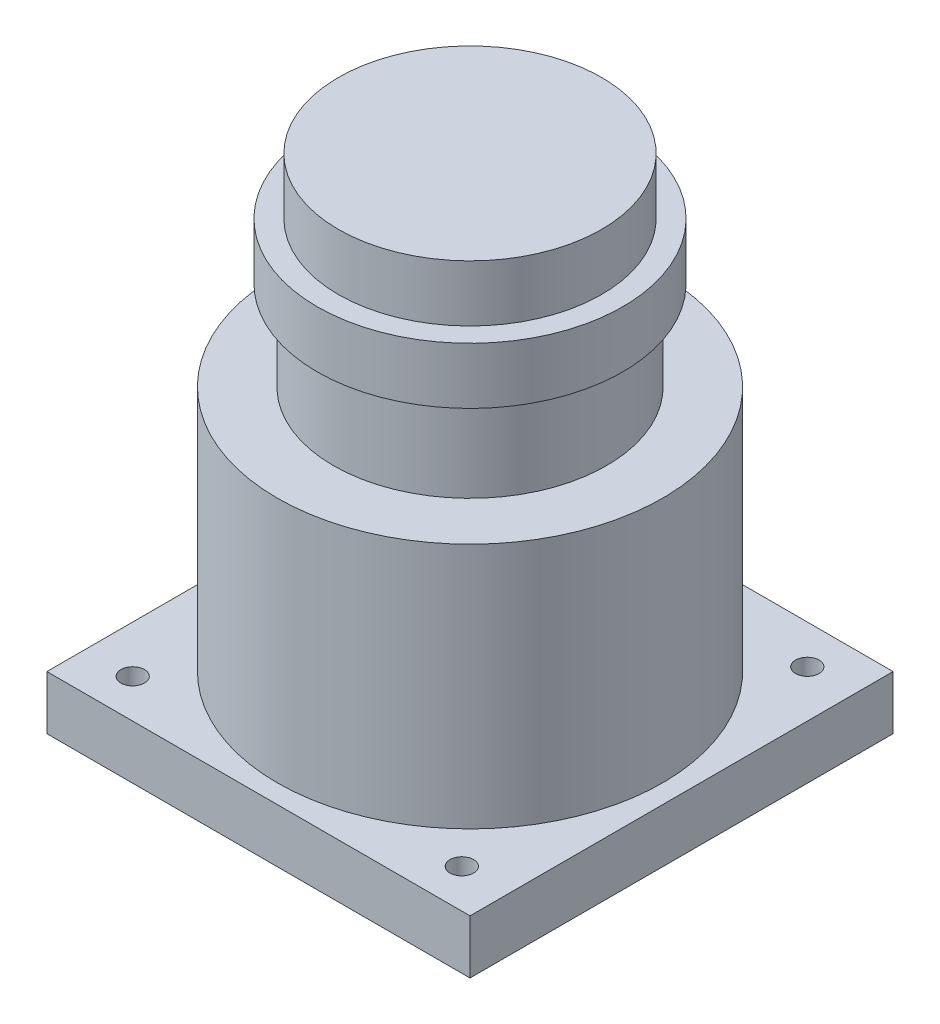
SolidWorks part; units mm, degrees
ref_plane "Front Plane" through (0, 0, 0) normal (0, 0, 1) x (1, 0, 0)
ref_plane "Top Plane" through (0, 0, 0) normal (0, 1, 0) x (1, 0, 0)
ref_plane "Right Plane" through (0, 0, 0) normal (1, 0, 0) x (0, 0, -1)
sketch "Sketch1" plane through (0, 0, 0) normal (0, 1, 0) x (1, 0, 0)
  line L1 (-45, -45) -> (45, -45)
  line L2 (-45, -45) -> (-45, 45)
  line L3 (-45, 45) -> (45, 45)
  line L4 (45, -45) -> (45, 45)
  line L5 (-45, -45) -> (45, 45) construction
  line L6 (-45, 45) -> (45, -45) construction
  point P0 (0, 0)
  dimension "D1" = 90
  dimension "D2" = 90
extrude "Boss-Extrude1" add sketch "Sketch1" along normal blind 11.45
sketch "Sketch2" plane through (0, 11.45, 0) normal (0, 1, 0) x (1, 0, 0)
  circle A0 centre (0, 0) radius 41
  dimension "D1" = 82
extrude "Boss-Extrude2" add sketch "Sketch2" along normal blind 52.45
sketch "Sketch3" plane through (0, 63.9, 0) normal (0, 1, 0) x (1, 0, 0)
  circle A0 centre (0, 0) radius 29.05
  dimension "D1" = 58.1
extrude "Boss-Extrude3" add sketch "Sketch3" along normal blind 19
sketch "Sketch4" plane through (0, 82.9, 0) normal (0, 1, 0) x (1, 0, 0)
  circle A0 centre (0, 0) radius 32.5
  dimension "D1" = 65
extrude "Boss-Extrude4" add sketch "Sketch4" along normal blind 12
sketch "Sketch5" plane through (0, 94.9, 0) normal (0, 1, 0) x (1, 0, 0)
  circle A0 centre (0, 0) radius 28
  dimension "D1" = 56
extrude "Boss-Extrude5" add sketch "Sketch5" along normal blind 12
sketch "Sketch6" plane through (0, 11.45, 0) normal (0, 1, 0) x (1, 0, 0)
  line L0 (-35, 36.75) -> (35, 36.75) construction
  line L1 (-35, 36.75) -> (-35, -36.75) construction
  circle A0 centre (-35, 36.75) radius 2.5
  circle A1 centre (35, 36.75) radius 2.5
  circle A2 centre (35, -36.75) radius 2.5
  circle A3 centre (-35, -36.75) radius 2.5
  point P4 (0, 0)
  dimension "D2" = 5
  dimension "D1" = 10
  dimension "D3" = 8.25
  dimension "D6" = 70
  dimension "D7" = 73.5
  dimension "D4" = 2
  dimension "D5" = 2
extrude "Cut-Extrude1" cut sketch "Sketch6" against normal through all
